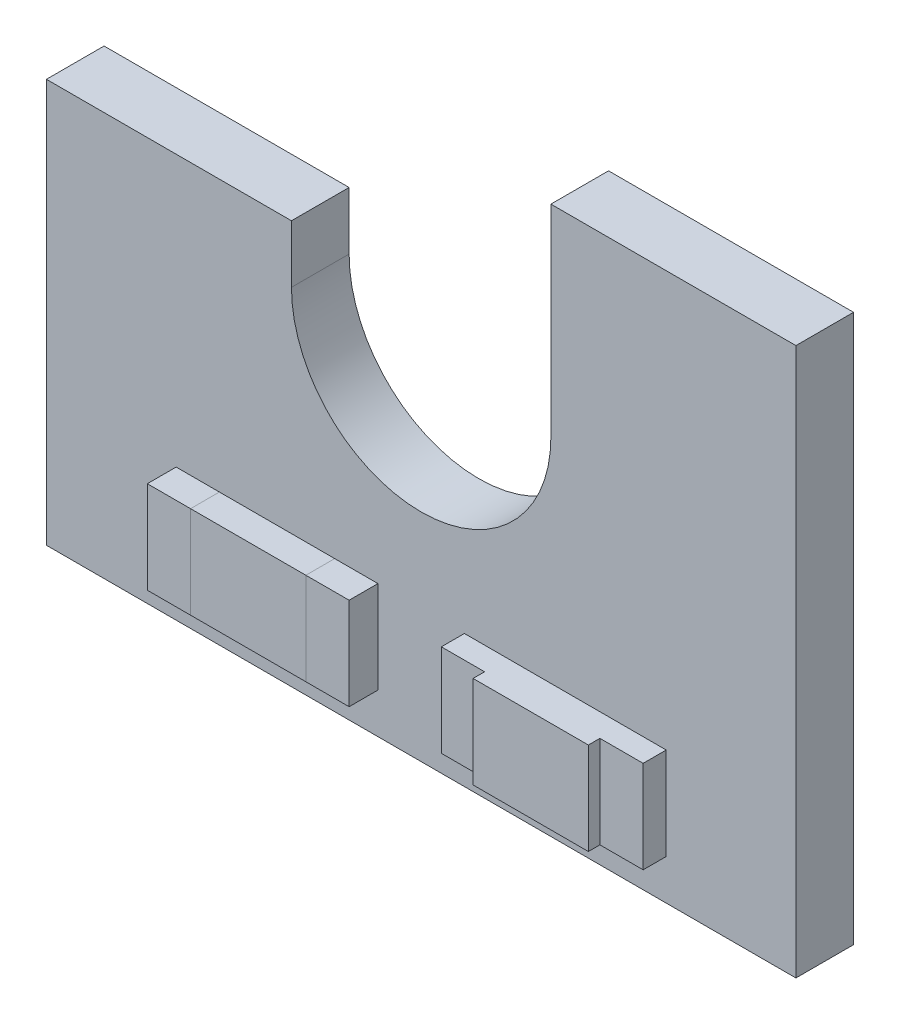
SolidWorks part; units mm, degrees
material "A-Glass Fiber"
ref_plane "Front Plane" through (0, 0, 0) normal (0, 0, 1) x (1, 0, 0)
ref_plane "Top Plane" through (0, 0, 0) normal (0, 1, 0) x (1, 0, 0)
ref_plane "Right Plane" through (0, 0, 0) normal (1, 0, 0) x (0, 0, -1)
sketch "BaseS" plane through (0, 0, 0) normal (0, 0, 1) x (1, 0, 0)
  line L1 (-6.5, 4.75) -> (6.5, 4.75)
  line L2 (-6.5, 4.75) -> (-6.5, -4.75)
  line L3 (-6.5, -4.75) -> (6.5, -4.75)
  line L4 (6.5, 4.75) -> (6.5, -4.75)
  line L5 (-6.5, 4.75) -> (6.5, -4.75) construction
  line L6 (-6.5, -4.75) -> (6.5, 4.75) construction
  point P0 (0, 0)
  dimension "Length" = 9.5
  dimension "Width" = 13
extrude "BASE" add sketch "BaseS" against normal blind 1
sketch "FastenerAccessS" plane through (0, 0, 0) normal (0, 0, 1) x (1, 0, 0)
  line L0 (0, -4.75) -> (0, 1.25) construction
  line L1 (-6.5, -4.75) -> (6.5, -4.75) construction
  line L2 (6.5, 4.75) -> (-6.5, 4.75) construction
  line L3 (-2.25, 4.75) -> (2.25, 4.75)
  line L4 (-2.25, 4.75) -> (-2.25, 1.25)
  line L6 (2.25, 4.75) -> (2.25, 1.25)
  arc A0 (-2.25, 1.25) -> (2.25, 1.25) centre (0, 1.25) ccw
  point P11 (0, 4.75)
  dimension "Dia" = 4.5
  dimension "YLoc" = 6
  dimension "HoleAccessWidth" = 4.5
extrude "FASTENER ACCESS" cut sketch "FastenerAccessS" against normal through all
sketch "SMDCapacitorBodyS" plane through (0, 0, 0) normal (0, 0, 1) x (1, 0, 0)
  line L0 (-6.5, -4.75) -> (6.5, -4.75) construction
  line L1 (-3.5, -2.45) -> (-1.5, -2.45)
  line L2 (-3.5, -2.45) -> (-3.5, -4.05)
  line L3 (-3.5, -4.05) -> (-1.5, -4.05)
  line L4 (-1.5, -2.45) -> (-1.5, -4.05)
  line L5 (-3.5, -2.45) -> (-1.5, -4.05) construction
  line L6 (-3.5, -4.05) -> (-1.5, -2.45) construction
  line L7 (-6.5, 4.75) -> (-6.5, -4.75) construction
  point P0 (-2.5, -3.25)
  dimension "YLoc" = 1.5
  dimension "Width" = 2
  dimension "Length" = 1.6
  dimension "XLoc" = 4
extrude "SMD CAPACITOR BODY" add sketch "SMDCapacitorBodyS" along normal blind 0.5 separate body
sketch "SMDCapacitorSolderBody1S" plane through (-3.5, -0.45, 0) normal (1, 0, 0) x (0, 1, 0)
  line L0 (-2, 0) -> (-3.6, 0) construction
  line L8 (-3.6, 0) -> (-2, 0)
  line L9 (-2, 0) -> (-2, 0.5)
  line L10 (-2, 0.5) -> (-3.6, 0.5)
  line L11 (-3.6, 0.5) -> (-3.6, 0)
  point P2 (-2, 0)
  point P7 (-3.6, 0)
  point P8 (-2, 0.7)
  point P9 (-3.6, 0.7)
  point P10 (-2, 0)
extrude "SMD CAPACITOR SOLDER BODY 1" add sketch "SMDCapacitorSolderBody1S" against normal blind 0.75 separate body
sketch "SMDCapacitorSolderBody2S" plane through (-1.5, -1.05, 0) normal (-1, 0, 0) x (0, 1, 0)
  line L1 (-3, 0) -> (-1.4, 0) construction
  line L2 (-1.4, -0.5) -> (-1.4, 0) construction
  line L3 (-3, -0.5) -> (-3, 0) construction
  line L8 (-1.4, 0) -> (-3, 0)
  line L9 (-3, 0) -> (-3, -0.5)
  line L10 (-3, -0.5) -> (-1.4, -0.5)
  line L11 (-1.4, -0.5) -> (-1.4, 0)
  point P2 (0, 0)
  point P4 (-1.4, 0)
  point P8 (-1.4, -0.7)
  point P9 (-1.4, -0.7)
  point P10 (-3, -0.7)
  point P11 (-3, 0)
  point P14 (-1.4, 0)
  point P15 (-1.4, -0.7)
  point P16 (-1.4, -0.7)
  point P17 (-1.4, 0)
  point P20 (-3, 0)
extrude "SMD CAPACITOR SOLDER BODY 2" add sketch "SMDCapacitorSolderBody2S" against normal blind 0.75 separate body
sketch "LEDS" plane through (0, 0, 0) normal (0, 0, 1) x (1, 0, 0)
  line L0 (-2.5, -3.25) -> (2.5, -3.25) construction
  line L1 (0.75, -2.45) -> (4.25, -2.45)
  line L2 (0.75, -2.45) -> (0.75, -4.05)
  line L3 (0.75, -4.05) -> (4.25, -4.05)
  line L4 (4.25, -2.45) -> (4.25, -4.05)
  line L5 (0.75, -2.45) -> (4.25, -4.05) construction
  line L6 (0.75, -4.05) -> (4.25, -2.45) construction
  line L7 (0, 0) -> (0, -3.25) construction
  point P0 (2.5, -3.25)
  dimension "Width" = 3.5
  dimension "Length" = 1.6
extrude "LED" add sketch "LEDS" along normal blind 0.4 separate body
sketch "LEDTS" plane through (0, 0, 0.4) normal (0, 0, 1) x (1, 0, 0)
  line L1 (1.5, -2.45) -> (3.5, -2.45)
  line L2 (1.5, -2.45) -> (1.5, -4.05)
  line L3 (1.5, -4.05) -> (3.5, -4.05)
  line L4 (3.5, -2.45) -> (3.5, -4.05)
  line L5 (1.5, -2.45) -> (3.5, -4.05) construction
  line L6 (1.5, -4.05) -> (3.5, -2.45) construction
  line L7 (0.75, -4.05) -> (4.25, -4.05) construction
  point P0 (2.5, -3.25)
  point P5 (3.3173, -3.9737)
  point P7 (0.75, -3.802)
  point P9 (0, 0)
  point P10 (0, 0)
  dimension "D1" = 2
extrude "LED TOP" add sketch "LEDTS" along normal blind 0.2
sketch "Sketch1" plane through (0, 0, 0) normal (0, 0, 1) x (1, 0, 0)
  line L0 (-2.25, 4.75) -> (-2.25, 1.25) construction
  line L1 (-2.25, 2.25) -> (-6.5, 2.25)
  line L2 (-2.25, 2.25) -> (-2.25, 4.75)
  line L3 (-2.25, 4.75) -> (-6.5, 4.75)
  line L4 (-6.5, 2.25) -> (-6.5, 4.75)
  line L5 (-6.5, -4.75) -> (6.5, -4.75) construction
  point P5 (-2.25, 2.7819)
  dimension "D1" = 2.5
  dimension "D2" = 7
extrude "PCB Left Cut" cut sketch "Sketch1" against normal through all
